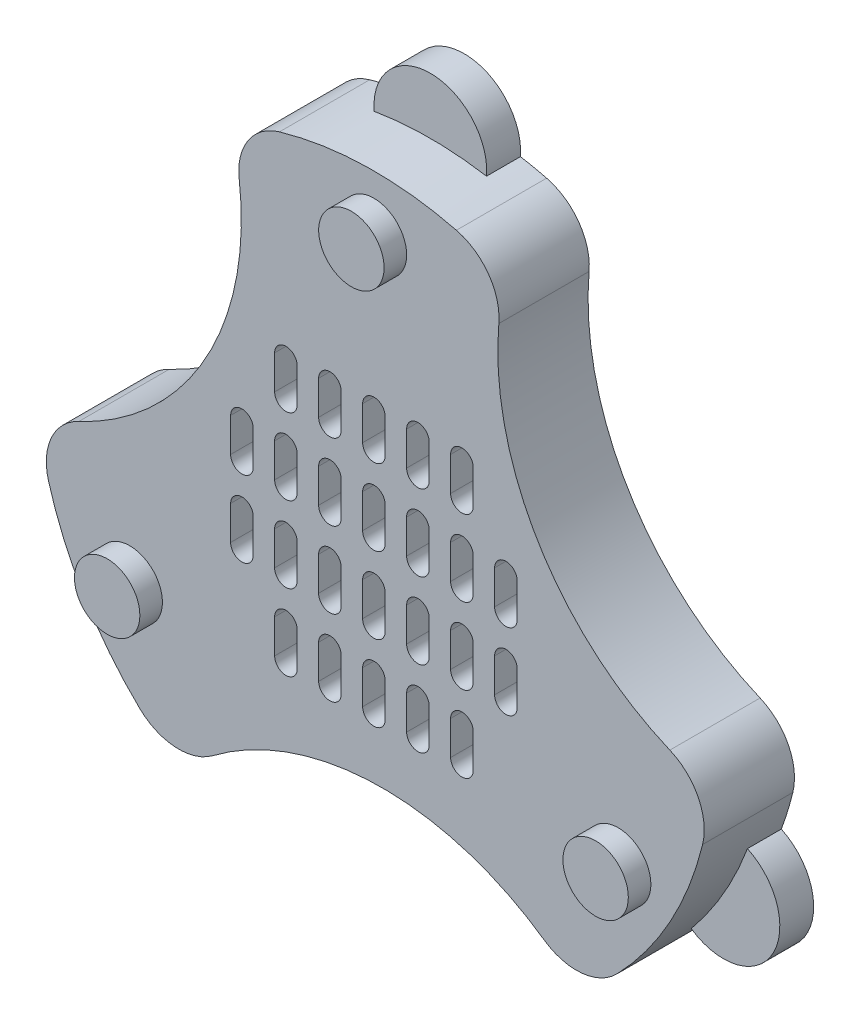
SolidWorks part; units mm, degrees
ref_plane "Спереди" through (0, 0, 0) normal (0, 0, 1) x (1, 0, 0)
ref_plane "Сверху" through (0, 0, 0) normal (0, 1, 0) x (1, 0, 0)
ref_plane "Справа" through (0, 0, 0) normal (1, 0, 0) x (0, 0, -1)
sketch "Sketch1" plane through (0, 0, 0) normal (0, 0, 1) x (1, 0, 0)
  line L0 (3.9, 6.755) -> (7.8, 0) construction
  line L2 (5.85, 10.1325) -> (11.7, 0) construction
  line L4 (7.8, 13.51) -> (15.6, 0) construction
  circle A61 centre (0, 0) radius 20
  circle A131 centre (0, 0) radius 1.25
  circle A484 centre (3.9, 0) radius 1.25
  circle A485 centre (7.8, 0) radius 1.25
  circle A486 centre (11.7, 0) radius 1.25
  circle A487 centre (15.6, 0) radius 1.25
  circle A488 centre (1.95, -3.3775) radius 1.25
  circle A489 centre (3.9, -6.755) radius 1.25
  circle A490 centre (5.85, -10.1325) radius 1.25
  circle A491 centre (7.8, -13.51) radius 1.25
  circle A492 centre (-1.95, -3.3775) radius 1.25
  circle A493 centre (-3.9, -6.755) radius 1.25
  circle A494 centre (-5.85, -10.1325) radius 1.25
  circle A495 centre (-7.8, -13.51) radius 1.25
  circle A496 centre (-3.9, 0) radius 1.25
  circle A497 centre (-7.8, 0) radius 1.25
  circle A498 centre (-11.7, 0) radius 1.25
  circle A499 centre (-15.6, 0) radius 1.25
  circle A500 centre (-1.95, 3.3775) radius 1.25
  circle A501 centre (-3.9, 6.755) radius 1.25
  circle A502 centre (-5.85, 10.1325) radius 1.25
  circle A503 centre (-7.8, 13.51) radius 1.25
  circle A504 centre (1.95, 3.3775) radius 1.25
  circle A505 centre (3.9, 6.755) radius 1.25
  circle A506 centre (5.85, 10.1325) radius 1.25
  circle A507 centre (7.8, 13.51) radius 1.25
  circle A508 centre (5.85, 3.3775) radius 1.25
  circle A509 centre (7.8, 6.755) radius 1.25
  circle A510 centre (9.75, 3.3775) radius 1.25
  circle A511 centre (11.7, 6.755) radius 1.25
  circle A512 centre (9.7491, 10.1341) radius 1.25
  circle A513 centre (13.6509, 3.3759) radius 1.25
  circle A514 centre (5.85, -3.3791) radius 1.25
  circle A515 centre (9.75, -3.3791) radius 1.25
  circle A516 centre (7.8, -6.7566) radius 1.25
  circle A517 centre (11.7, -6.7566) radius 1.25
  circle A518 centre (9.7491, -10.1356) radius 1.25
  circle A519 centre (13.6509, -3.3775) radius 1.25
  circle A520 centre (-0.0013, -6.7573) radius 1.25
  circle A521 centre (1.9487, -10.1348) radius 1.25
  circle A522 centre (-1.9513, -10.1348) radius 1.25
  circle A523 centre (-0.0013, -13.5123) radius 1.25
  circle A524 centre (-3.9032, -13.5123) radius 1.25
  circle A525 centre (3.9005, -13.5123) radius 1.25
  circle A526 centre (-5.8527, -3.3791) radius 1.25
  circle A527 centre (-7.8027, -6.7566) radius 1.25
  circle A528 centre (-9.7527, -3.3791) radius 1.25
  circle A529 centre (-11.7027, -6.7566) radius 1.25
  circle A530 centre (-13.6536, -3.3775) radius 1.25
  circle A531 centre (-9.7518, -10.1356) radius 1.25
  circle A532 centre (-5.8527, 3.3775) radius 1.25
  circle A533 centre (-9.7527, 3.3775) radius 1.25
  circle A534 centre (-7.8027, 6.755) radius 1.25
  circle A535 centre (-11.7027, 6.755) radius 1.25
  circle A536 centre (-9.7518, 10.1341) radius 1.25
  circle A537 centre (-13.6536, 3.3759) radius 1.25
  circle A538 centre (-0.0014, 6.7558) radius 1.25
  circle A539 centre (-1.9514, 10.1333) radius 1.25
  circle A540 centre (1.9486, 10.1333) radius 1.25
  circle A541 centre (-0.0014, 13.5108) radius 1.25
  circle A542 centre (3.9005, 13.5108) radius 1.25
  circle A543 centre (-3.9032, 13.5108) radius 1.25
  circle A544 centre (13.65, -1.1258) radius 2.2517 construction
  circle A545 centre (11.7009, -4.5044) radius 2.2522 construction
  circle A546 centre (9.75, -7.8834) radius 2.2522 construction
  circle A547 centre (7.7987, -11.2591) radius 2.2509 construction
  circle A548 centre (13.65, -1.1258) radius 0.65
  circle A549 centre (11.7009, -4.5044) radius 0.65
  circle A550 centre (9.75, -7.8834) radius 0.65
  circle A551 centre (7.7987, -11.2591) radius 0.65
  circle A552 centre (9.75, -1.1258) radius 0.65
  circle A553 centre (7.8009, -4.5044) radius 0.65
  circle A554 centre (5.85, -7.8834) radius 0.65
  circle A555 centre (3.8987, -11.2591) radius 0.65
  circle A556 centre (5.85, -1.1258) radius 0.65
  circle A557 centre (3.9009, -4.5044) radius 0.65
  circle A558 centre (1.95, -7.8834) radius 0.65
  circle A559 centre (-0.0013, -11.2591) radius 0.65
  circle A560 centre (1.95, -1.1258) radius 0.65
  circle A561 centre (0.0009, -4.5044) radius 0.65
  circle A562 centre (-1.95, -7.8834) radius 0.65
  circle A563 centre (-3.9013, -11.2591) radius 0.65
  circle A564 centre (-1.95, -1.1258) radius 0.65
  circle A565 centre (-3.8991, -4.5044) radius 0.65
  circle A566 centre (-5.85, -7.8834) radius 0.65
  circle A567 centre (-7.8013, -11.2591) radius 0.65
  circle A568 centre (-5.85, -1.1258) radius 0.65
  circle A569 centre (-7.7991, -4.5044) radius 0.65
  circle A570 centre (-9.75, -7.8834) radius 0.65
  circle A572 centre (-9.75, -1.1258) radius 0.65
  circle A573 centre (-11.6991, -4.5044) radius 0.65
  circle A576 centre (-13.65, -1.1258) radius 0.65
  circle A587 centre (0, 2.2517) radius 2.2517 construction
  circle A588 centre (0, 2.2517) radius 0.65
  circle A589 centre (3.9, 2.2517) radius 0.65
  circle A590 centre (7.8, 2.2517) radius 0.65
  circle A591 centre (11.7, 2.2517) radius 0.65
  circle A592 centre (15.6, 2.2517) radius 0.65
  circle A593 centre (1.9491, 5.6297) radius 2.2522 construction
  circle A594 centre (1.9491, 5.6297) radius 0.65
  circle A595 centre (5.8491, 5.6297) radius 0.65
  circle A596 centre (9.7491, 5.6297) radius 0.65
  circle A597 centre (13.6491, 5.6297) radius 0.65
  circle A598 centre (3.8991, 9.0072) radius 2.2522 construction
  circle A599 centre (3.8991, 9.0072) radius 0.65
  circle A600 centre (7.7991, 9.0072) radius 0.65
  circle A601 centre (11.6991, 9.0072) radius 0.65
  circle A602 centre (5.85, 12.3842) radius 2.2517 construction
  circle A603 centre (5.85, 12.3842) radius 0.65
  circle A604 centre (9.75, 12.3842) radius 0.65
  circle A605 centre (5.85, -14.6358) radius 0.65
  circle A606 centre (1.9509, -14.6353) radius 0.65
  circle A607 centre (-1.9491, -14.6353) radius 0.65
  circle A608 centre (-5.85, -14.6358) radius 0.65
  circle A609 centre (-15.6, 2.2517) radius 0.65
  circle A610 centre (-13.65, 5.6281) radius 0.65
  circle A611 centre (-11.7, 9.0056) radius 0.65
  circle A612 centre (-9.75, 12.3842) radius 0.65
  circle A613 centre (-5.85, 12.3842) radius 0.65
  circle A614 centre (-1.95, 12.3842) radius 0.65
  circle A615 centre (1.95, 12.3842) radius 0.65
  circle A616 centre (-7.8, 9.0056) radius 0.65
  circle A617 centre (-9.75, 5.6281) radius 0.65
  circle A618 centre (-11.7, 2.2517) radius 0.65
  circle A619 centre (-3.9, 9.0056) radius 0.65
  circle A620 centre (-5.85, 5.6281) radius 0.65
  circle A621 centre (-7.8, 2.2517) radius 0.65
  circle A622 centre (0, 9.0056) radius 0.65
  circle A623 centre (-1.95, 5.6281) radius 0.65
  circle A624 centre (-3.9, 2.2517) radius 0.65
  circle A625 centre (-15.5991, -4.5044) radius 0.65
  circle A626 centre (-13.65, -7.8834) radius 0.65
  circle A627 centre (-17.55, -7.8834) radius 0.65
  circle A628 centre (-19.5013, -11.2591) radius 0.65
  circle A629 centre (-15.6013, -11.2591) radius 0.65
  circle A630 centre (-11.7013, -11.2591) radius 0.65
  point P51 (0, 0)
  point P125 (-0.0013, -0.0008)
  point P231 (0, 0)
  dimension "D1" = 5
  dimension "D3" = 6
  dimension "D5" = 8
  dimension "D7" = 4
  dimension "D11" = 4
  dimension "D2" = 6
  dimension "D6" = 5
  dimension "D8" = 3
  dimension "D9" = 2
  dimension "D4" = 1.3
  dimension "D10" = 3
ref_plane "Plane1" through (0, 0, 10) normal (0, 0, 1) x (1, 0, 0)
sketch "Sketch2" plane through (0, 0, 10) normal (0, 0, 1) x (1, 0, 0)
  line L0 (-7.8, 13.51) -> (-7.8027, 6.755) construction
  line L1 (-9.7518, 10.1341) -> (-5.85, 10.1325) construction
  line L2 (-7.8008, 11.6325) -> (-7.8019, 8.6325) construction
  line L3 (-6.8008, 11.6321) -> (-6.8019, 8.6321)
  line L4 (-8.8008, 11.6329) -> (-8.8019, 8.6329)
  line L5 (-4.9008, 11.6329) -> (-4.9019, 8.6329)
  line L6 (-2.9008, 11.6321) -> (-2.9019, 8.6321)
  line L7 (-3.9008, 11.6325) -> (-3.9019, 8.6325) construction
  line L8 (-1.0008, 11.6329) -> (-1.0019, 8.6329)
  line L9 (0.9992, 11.6321) -> (0.9981, 8.6321)
  line L10 (-0.0008, 11.6325) -> (-0.0019, 8.6325) construction
  line L11 (2.8992, 11.6329) -> (2.8981, 8.6329)
  line L12 (4.8992, 11.6321) -> (4.8981, 8.6321)
  line L13 (3.8992, 11.6325) -> (3.8981, 8.6325) construction
  line L14 (6.7992, 11.6329) -> (6.7981, 8.6329)
  line L15 (8.7992, 11.6321) -> (8.7981, 8.6321)
  line L16 (7.7992, 11.6325) -> (7.7981, 8.6325) construction
  line L17 (-9.7518, 10.1341) -> (-9.7527, 3.3775) construction
  line L18 (-11.7027, 6.755) -> (-7.8027, 6.755) construction
  line L19 (-10.7035, 1.877) -> (-10.702, 4.877)
  line L22 (-9.7527, 3.3775) -> (-5.8527, 3.3775) construction
  line L25 (-7.8027, 6.755) -> (-7.8, 0) construction
  line L26 (-7.8035, 1.8775) -> (-7.8019, 4.8775) construction
  line L27 (-8.8035, 1.878) -> (-8.8019, 4.878)
  line L28 (-6.8035, 1.877) -> (-6.8019, 4.877)
  line L29 (-2.9035, 1.877) -> (-2.9019, 4.877)
  line L30 (-4.9035, 1.878) -> (-4.9019, 4.878)
  line L31 (-3.9035, 1.8775) -> (-3.9019, 4.8775) construction
  line L32 (0.9965, 1.877) -> (0.9981, 4.877)
  line L33 (-1.0035, 1.878) -> (-1.0019, 4.878)
  line L34 (-0.0035, 1.8775) -> (-0.0019, 4.8775) construction
  line L35 (4.8965, 1.877) -> (4.8981, 4.877)
  line L36 (2.8965, 1.878) -> (2.8981, 4.878)
  line L37 (3.8965, 1.8775) -> (3.8981, 4.8775) construction
  line L38 (8.7965, 1.877) -> (8.7981, 4.877)
  line L39 (6.7965, 1.878) -> (6.7981, 4.878)
  line L40 (7.7965, 1.8775) -> (7.7981, 4.8775) construction
  line L41 (12.6965, 1.877) -> (12.6981, 4.877)
  line L42 (10.6965, 1.878) -> (10.6981, 4.878)
  line L43 (11.6965, 1.8775) -> (11.6981, 4.8775) construction
  line L44 (-12.7035, 1.878) -> (-12.7019, 4.878)
  line L45 (-11.7035, 1.8775) -> (-11.702, 4.8775) construction
  line L46 (-9.7527, -3.3791) -> (-5.8527, -3.3791) construction
  line L47 (-7.8, 0) -> (-7.8027, -6.7566) construction
  line L48 (-7.8046, -4.8791) -> (-7.8008, -1.8791) construction
  line L49 (-8.8046, -4.8778) -> (-8.8008, -1.8778)
  line L50 (-6.8046, -4.8804) -> (-6.8008, -1.8804)
  line L51 (-2.9046, -4.8804) -> (-2.9008, -1.8804)
  line L52 (-4.9046, -4.8778) -> (-4.9008, -1.8778)
  line L53 (-3.9046, -4.8791) -> (-3.9008, -1.8791) construction
  line L54 (0.9954, -4.8804) -> (0.9992, -1.8804)
  line L55 (-1.0046, -4.8778) -> (-1.0008, -1.8778)
  line L56 (-0.0046, -4.8791) -> (-0.0008, -1.8791) construction
  line L57 (4.8954, -4.8804) -> (4.8992, -1.8804)
  line L58 (2.8954, -4.8778) -> (2.8992, -1.8778)
  line L59 (3.8954, -4.8791) -> (3.8992, -1.8791) construction
  line L60 (8.7954, -4.8804) -> (8.7992, -1.8804)
  line L61 (6.7954, -4.8778) -> (6.7992, -1.8778)
  line L62 (7.7954, -4.8791) -> (7.7992, -1.8791) construction
  line L63 (12.6954, -4.8804) -> (12.6992, -1.8804)
  line L64 (10.6954, -4.8778) -> (10.6992, -1.8778)
  line L65 (11.6954, -4.8791) -> (11.6992, -1.8791) construction
  line L66 (-10.7046, -4.8804) -> (-10.7008, -1.8804)
  line L67 (-12.7046, -4.8778) -> (-12.7008, -1.8778)
  line L68 (-11.7046, -4.8791) -> (-11.7008, -1.8791) construction
  line L69 (-9.7518, -10.1356) -> (-5.482, -10.1356) construction
  line L70 (-7.8027, -6.7566) -> (-7.8, -13.51) construction
  line L71 (-7.8007, -8.6356) -> (-7.8007, -11.6356) construction
  line L72 (-6.8007, -8.6356) -> (-6.8007, -11.6356)
  line L73 (-8.8007, -8.6356) -> (-8.8007, -11.6356)
  line L74 (-4.9007, -8.6356) -> (-4.9007, -11.6356)
  line L75 (-2.9007, -8.6356) -> (-2.9007, -11.6356)
  line L76 (-3.9007, -8.6356) -> (-3.9007, -11.6356) construction
  line L77 (-1.0007, -8.6356) -> (-1.0007, -11.6356)
  line L78 (0.9993, -8.6356) -> (0.9993, -11.6356)
  line L79 (-0.0007, -8.6356) -> (-0.0007, -11.6356) construction
  line L80 (2.8993, -8.6356) -> (2.8993, -11.6356)
  line L81 (4.8993, -8.6356) -> (4.8993, -11.6356)
  line L82 (3.8993, -8.6356) -> (3.8993, -11.6356) construction
  line L83 (6.7993, -8.6356) -> (6.7993, -11.6356)
  line L84 (8.7993, -8.6356) -> (8.7993, -11.6356)
  line L85 (7.7993, -8.6356) -> (7.7993, -11.6356) construction
  arc A0 (-6.8008, 11.6321) -> (-8.8008, 11.6329) centre (-7.8008, 11.6325) ccw
  arc A1 (-8.8019, 8.6329) -> (-6.8019, 8.6321) centre (-7.8019, 8.6325) ccw
  arc A2 (-2.9008, 11.6321) -> (-4.9008, 11.6329) centre (-3.9008, 11.6325) ccw
  arc A3 (-4.9019, 8.6329) -> (-2.9019, 8.6321) centre (-3.9019, 8.6325) ccw
  arc A4 (0.9992, 11.6321) -> (-1.0008, 11.6329) centre (-0.0008, 11.6325) ccw
  arc A5 (-1.0019, 8.6329) -> (0.9981, 8.6321) centre (-0.0019, 8.6325) ccw
  arc A6 (4.8992, 11.6321) -> (2.8992, 11.6329) centre (3.8992, 11.6325) ccw
  arc A7 (2.8981, 8.6329) -> (4.8981, 8.6321) centre (3.8981, 8.6325) ccw
  arc A8 (8.7992, 11.6321) -> (6.7992, 11.6329) centre (7.7992, 11.6325) ccw
  arc A9 (6.7981, 8.6329) -> (8.7981, 8.6321) centre (7.7981, 8.6325) ccw
  arc A14 (-8.8035, 1.878) -> (-6.8035, 1.877) centre (-7.8035, 1.8775) ccw
  arc A15 (-6.8019, 4.877) -> (-8.8019, 4.878) centre (-7.8019, 4.8775) ccw
  arc A16 (-4.9035, 1.878) -> (-2.9035, 1.877) centre (-3.9035, 1.8775) ccw
  arc A17 (-2.9019, 4.877) -> (-4.9019, 4.878) centre (-3.9019, 4.8775) ccw
  arc A18 (-1.0035, 1.878) -> (0.9965, 1.877) centre (-0.0035, 1.8775) ccw
  arc A19 (0.9981, 4.877) -> (-1.0019, 4.878) centre (-0.0019, 4.8775) ccw
  arc A20 (2.8965, 1.878) -> (4.8965, 1.877) centre (3.8965, 1.8775) ccw
  arc A21 (4.8981, 4.877) -> (2.8981, 4.878) centre (3.8981, 4.8775) ccw
  arc A22 (6.7965, 1.878) -> (8.7965, 1.877) centre (7.7965, 1.8775) ccw
  arc A23 (8.7981, 4.877) -> (6.7981, 4.878) centre (7.7981, 4.8775) ccw
  arc A24 (10.6965, 1.878) -> (12.6965, 1.877) centre (11.6965, 1.8775) ccw
  arc A25 (12.6981, 4.877) -> (10.6981, 4.878) centre (11.6981, 4.8775) ccw
  arc A26 (-12.7035, 1.878) -> (-10.7035, 1.877) centre (-11.7035, 1.8775) ccw
  arc A27 (-10.702, 4.877) -> (-12.7019, 4.878) centre (-11.702, 4.8775) ccw
  arc A28 (-8.8046, -4.8778) -> (-6.8046, -4.8804) centre (-7.8046, -4.8791) ccw
  arc A29 (-6.8008, -1.8804) -> (-8.8008, -1.8778) centre (-7.8008, -1.8791) ccw
  arc A30 (-4.9046, -4.8778) -> (-2.9046, -4.8804) centre (-3.9046, -4.8791) ccw
  arc A31 (-2.9008, -1.8804) -> (-4.9008, -1.8778) centre (-3.9008, -1.8791) ccw
  arc A32 (-1.0046, -4.8778) -> (0.9954, -4.8804) centre (-0.0046, -4.8791) ccw
  arc A33 (0.9992, -1.8804) -> (-1.0008, -1.8778) centre (-0.0008, -1.8791) ccw
  arc A34 (2.8954, -4.8778) -> (4.8954, -4.8804) centre (3.8954, -4.8791) ccw
  arc A35 (4.8992, -1.8804) -> (2.8992, -1.8778) centre (3.8992, -1.8791) ccw
  arc A36 (6.7954, -4.8778) -> (8.7954, -4.8804) centre (7.7954, -4.8791) ccw
  arc A37 (8.7992, -1.8804) -> (6.7992, -1.8778) centre (7.7992, -1.8791) ccw
  arc A38 (10.6954, -4.8778) -> (12.6954, -4.8804) centre (11.6954, -4.8791) ccw
  arc A39 (12.6992, -1.8804) -> (10.6992, -1.8778) centre (11.6992, -1.8791) ccw
  arc A40 (-12.7046, -4.8778) -> (-10.7046, -4.8804) centre (-11.7046, -4.8791) ccw
  arc A41 (-10.7008, -1.8804) -> (-12.7008, -1.8778) centre (-11.7008, -1.8791) ccw
  arc A42 (-6.8007, -8.6356) -> (-8.8007, -8.6356) centre (-7.8007, -8.6356) ccw
  arc A43 (-8.8007, -11.6356) -> (-6.8007, -11.6356) centre (-7.8007, -11.6356) ccw
  arc A44 (-2.9007, -8.6356) -> (-4.9007, -8.6356) centre (-3.9007, -8.6356) ccw
  arc A45 (-4.9007, -11.6356) -> (-2.9007, -11.6356) centre (-3.9007, -11.6356) ccw
  arc A46 (0.9993, -8.6356) -> (-1.0007, -8.6356) centre (-0.0007, -8.6356) ccw
  arc A47 (-1.0007, -11.6356) -> (0.9993, -11.6356) centre (-0.0007, -11.6356) ccw
  arc A48 (4.8993, -8.6356) -> (2.8993, -8.6356) centre (3.8993, -8.6356) ccw
  arc A49 (2.8993, -11.6356) -> (4.8993, -11.6356) centre (3.8993, -11.6356) ccw
  arc A50 (8.7993, -8.6356) -> (6.7993, -8.6356) centre (7.7993, -8.6356) ccw
  arc A51 (6.7993, -11.6356) -> (8.7993, -11.6356) centre (7.7993, -11.6356) ccw
  circle A52 centre (0, 0) radius 16.85 construction
  circle A53 centre (0, 0) radius 18.85
  point P10 (-7.8014, 10.1325)
  point P18 (-3.9014, 10.1325)
  point P25 (-0.0014, 10.1325)
  point P32 (3.8986, 10.1325)
  point P39 (7.7986, 10.1325)
  point P50 (-11.7027, 3.3775)
  point P58 (-7.8027, 3.3775)
  point P68 (-3.9027, 3.3775)
  point P75 (-0.0027, 3.3775)
  point P82 (3.8973, 3.3775)
  point P89 (7.7973, 3.3775)
  point P96 (11.6973, 3.3775)
  point P108 (-7.8027, -3.3791)
  point P116 (-3.9027, -3.3791)
  point P123 (-0.0027, -3.3791)
  point P130 (3.8973, -3.3791)
  point P137 (7.7973, -3.3791)
  point P144 (11.6973, -3.3791)
  point P151 (-11.7027, -3.3791)
  point P162 (-7.8007, -10.1356)
  point P170 (-3.9007, -10.1356)
  point P177 (-0.0007, -10.1356)
  point P184 (3.8993, -10.1356)
  point P191 (7.7993, -10.1356)
  dimension "D1" = 2
  dimension "D15" = 2
  dimension "D2" = 3
  dimension "D4" = 2
  dimension "D5" = 3
  dimension "D6" = 2
  dimension "D7" = 3
  dimension "D9" = 2
  dimension "D12" = 3
  dimension "D13" = 2
  dimension "D3" = 5
  dimension "D8" = 6
  dimension "D10" = 6
  dimension "D11" = 2
  dimension "D14" = 5
extrude "Boss-Extrude1" add sketch "Sketch2" along normal blind 8
sketch "Sketch3" plane through (0, 0, 18) normal (0, 0, 1) x (1, 0, 0)
  circle A0 centre (0, 0) radius 17.6
  circle A1 centre (0, 0) radius 30
extrude "Boss-Extrude2" add sketch "Sketch3" against normal up to surface (8 mm away) up to face at (3.8993, -10.1356, 10)
sketch "Sketch4" plane through (0, 0, 18) normal (0, 0, 1) x (1, 0, 0)
  circle A0 centre (0, 0) radius 25 construction
  circle A1 centre (0, 25) radius 2.9
  circle A2 centre (21.6506, -12.5) radius 2.9
  circle A3 centre (-21.6506, -12.5) radius 2.9
  point P11 (0, 0)
  dimension "D1" = 3
extrude "Boss-Extrude3" add sketch "Sketch4" along normal blind 2
sketch "Sketch6" plane through (0, 0, 10) normal (0, 0, -1) x (-1, 0, 0)
  circle A0 centre (0, 30) radius 5
  circle A1 centre (0, 0) radius 30 construction
  circle A2 centre (25.9808, -15) radius 5
  circle A3 centre (-25.9808, -15) radius 5
  point P10 (0, 0)
  dimension "D1" = 3
extrude "Boss-Extrude4" add sketch "Sketch6" against normal blind 3
sketch "Sketch5" plane through (0, 0, 10) normal (0, 0, -1) x (-1, 0, 0)
  circle A0 centre (0, 25) radius 3
  circle A1 centre (21.6506, -12.5) radius 3
  circle A2 centre (-21.6506, -12.5) radius 3
extrude "Cut-Extrude1" cut sketch "Sketch5" against normal blind 3
sketch "Sketch7" plane through (0, 0, 10) normal (0, 0, -1) x (-1, 0, 0)
  line L0 (0, 0) -> (-35.9801, 21.6664) construction
  circle A0 centre (0, 0) radius 42 construction
  circle A1 centre (-35.9801, 21.6664) radius 25
  circle A2 centre (36.7537, 20.3265) radius 25
  circle A3 centre (-0.7736, -41.9929) radius 25
  point P11 (0, 0)
  dimension "D1" = 3
extrude "Cut-Extrude2" cut sketch "Sketch7" against normal blind 8
fillet "Fillet1" radius 5 6 edges at (-29.7735, -3.6793, 14) (-12.7099, 27.1746, 14) (18.0731, -23.945, 14) (-17.1789, -24.5944, 14) (11.7004, 27.6243, 14) (29.8888, -2.5802, 14)
sketch "Sketch8"
sketch_block_instance "Block1-1"
sketch_block "Block1" parameters "D1"=2, "D2"=3
sketch_block_instance "Block3-1"
sketch_block "Block3" parameters "D1"=2, "D2"=3
sketch "Sketch9" plane through (0, 0, 0) normal (0, 0, 1) x (1, 0, 0)
  line L0 (-7.8, 13.51) -> (-7.8027, 6.755) construction
  line L1 (-9.7518, 10.1341) -> (-5.85, 10.1325) construction
  line L2 (-7.8008, 11.6325) -> (-7.8019, 8.6325) construction
  line L3 (-6.8008, 11.6321) -> (-6.8019, 8.6321)
  line L4 (-8.8008, 11.6329) -> (-8.8019, 8.6329)
  line L5 (-4.9008, 11.6329) -> (-4.9019, 8.6329)
  line L6 (-2.9008, 11.6321) -> (-2.9019, 8.6321)
  line L7 (-3.9008, 11.6325) -> (-3.9019, 8.6325) construction
  line L8 (-1.0008, 11.6329) -> (-1.0019, 8.6329)
  line L9 (0.9992, 11.6321) -> (0.9981, 8.6321)
  line L10 (-0.0008, 11.6325) -> (-0.0019, 8.6325) construction
  line L11 (2.8992, 11.6329) -> (2.8981, 8.6329)
  line L12 (4.8992, 11.6321) -> (4.8981, 8.6321)
  line L13 (3.8992, 11.6325) -> (3.8981, 8.6325) construction
  line L14 (6.7992, 11.6329) -> (6.7981, 8.6329)
  line L15 (8.7992, 11.6321) -> (8.7981, 8.6321)
  line L16 (7.7992, 11.6325) -> (7.7981, 8.6325) construction
  line L17 (-9.7518, 10.1341) -> (-9.7527, 3.3775) construction
  line L18 (-11.7027, 6.755) -> (-7.8027, 6.755) construction
  line L19 (-10.7035, 1.877) -> (-10.702, 4.877)
  line L22 (-9.7527, 3.3775) -> (-5.8527, 3.3775) construction
  line L25 (-7.8027, 6.755) -> (-7.8, 0) construction
  line L26 (-7.8035, 1.8775) -> (-7.8019, 4.8775) construction
  line L27 (-8.8035, 1.878) -> (-8.8019, 4.878)
  line L28 (-6.8035, 1.877) -> (-6.8019, 4.877)
  line L29 (-2.9035, 1.877) -> (-2.9019, 4.877)
  line L30 (-4.9035, 1.878) -> (-4.9019, 4.878)
  line L31 (-3.9035, 1.8775) -> (-3.9019, 4.8775) construction
  line L32 (0.9965, 1.877) -> (0.9981, 4.877)
  line L33 (-1.0035, 1.878) -> (-1.0019, 4.878)
  line L34 (-0.0035, 1.8775) -> (-0.0019, 4.8775) construction
  line L35 (4.8965, 1.877) -> (4.8981, 4.877)
  line L36 (2.8965, 1.878) -> (2.8981, 4.878)
  line L37 (3.8965, 1.8775) -> (3.8981, 4.8775) construction
  line L38 (8.7965, 1.877) -> (8.7981, 4.877)
  line L39 (6.7965, 1.878) -> (6.7981, 4.878)
  line L40 (7.7965, 1.8775) -> (7.7981, 4.8775) construction
  line L41 (12.6965, 1.877) -> (12.6981, 4.877)
  line L42 (10.6965, 1.878) -> (10.6981, 4.878)
  line L43 (11.6965, 1.8775) -> (11.6981, 4.8775) construction
  line L44 (-12.7035, 1.878) -> (-12.7019, 4.878)
  line L45 (-11.7035, 1.8775) -> (-11.702, 4.8775) construction
  line L46 (-9.7527, -3.3791) -> (-5.8527, -3.3791) construction
  line L47 (-7.8, 0) -> (-7.8027, -6.7566) construction
  line L48 (-7.8046, -4.8791) -> (-7.8008, -1.8791) construction
  line L49 (-8.8046, -4.8778) -> (-8.8008, -1.8778)
  line L50 (-6.8046, -4.8804) -> (-6.8008, -1.8804)
  line L51 (-2.9046, -4.8804) -> (-2.9008, -1.8804)
  line L52 (-4.9046, -4.8778) -> (-4.9008, -1.8778)
  line L53 (-3.9046, -4.8791) -> (-3.9008, -1.8791) construction
  line L54 (0.9954, -4.8804) -> (0.9992, -1.8804)
  line L55 (-1.0046, -4.8778) -> (-1.0008, -1.8778)
  line L56 (-0.0046, -4.8791) -> (-0.0008, -1.8791) construction
  line L57 (4.8954, -4.8804) -> (4.8992, -1.8804)
  line L58 (2.8954, -4.8778) -> (2.8992, -1.8778)
  line L59 (3.8954, -4.8791) -> (3.8992, -1.8791) construction
  line L60 (8.7954, -4.8804) -> (8.7992, -1.8804)
  line L61 (6.7954, -4.8778) -> (6.7992, -1.8778)
  line L62 (7.7954, -4.8791) -> (7.7992, -1.8791) construction
  line L63 (12.6954, -4.8804) -> (12.6992, -1.8804)
  line L64 (10.6954, -4.8778) -> (10.6992, -1.8778)
  line L65 (11.6954, -4.8791) -> (11.6992, -1.8791) construction
  line L66 (-10.7046, -4.8804) -> (-10.7008, -1.8804)
  line L67 (-12.7046, -4.8778) -> (-12.7008, -1.8778)
  line L68 (-11.7046, -4.8791) -> (-11.7008, -1.8791) construction
  line L69 (-9.7518, -10.1356) -> (-5.482, -10.1356) construction
  line L70 (-7.8027, -6.7566) -> (-7.8, -13.51) construction
  line L71 (-7.8007, -8.6356) -> (-7.8007, -11.6356) construction
  line L72 (-6.8007, -8.6356) -> (-6.8007, -11.6356)
  line L73 (-8.8007, -8.6356) -> (-8.8007, -11.6356)
  line L74 (-4.9007, -8.6356) -> (-4.9007, -11.6356)
  line L75 (-2.9007, -8.6356) -> (-2.9007, -11.6356)
  line L76 (-3.9007, -8.6356) -> (-3.9007, -11.6356) construction
  line L77 (-1.0007, -8.6356) -> (-1.0007, -11.6356)
  line L78 (0.9993, -8.6356) -> (0.9993, -11.6356)
  line L79 (-0.0007, -8.6356) -> (-0.0007, -11.6356) construction
  line L80 (2.8993, -8.6356) -> (2.8993, -11.6356)
  line L81 (4.8993, -8.6356) -> (4.8993, -11.6356)
  line L82 (3.8993, -8.6356) -> (3.8993, -11.6356) construction
  line L83 (6.7993, -8.6356) -> (6.7993, -11.6356)
  line L84 (8.7993, -8.6356) -> (8.7993, -11.6356)
  line L85 (7.7993, -8.6356) -> (7.7993, -11.6356) construction
  arc A0 (-6.8008, 11.6321) -> (-8.8008, 11.6329) centre (-7.8008, 11.6325) ccw
  arc A1 (-8.8019, 8.6329) -> (-6.8019, 8.6321) centre (-7.8019, 8.6325) ccw
  arc A2 (-2.9008, 11.6321) -> (-4.9008, 11.6329) centre (-3.9008, 11.6325) ccw
  arc A3 (-4.9019, 8.6329) -> (-2.9019, 8.6321) centre (-3.9019, 8.6325) ccw
  arc A4 (0.9992, 11.6321) -> (-1.0008, 11.6329) centre (-0.0008, 11.6325) ccw
  arc A5 (-1.0019, 8.6329) -> (0.9981, 8.6321) centre (-0.0019, 8.6325) ccw
  arc A6 (4.8992, 11.6321) -> (2.8992, 11.6329) centre (3.8992, 11.6325) ccw
  arc A7 (2.8981, 8.6329) -> (4.8981, 8.6321) centre (3.8981, 8.6325) ccw
  arc A8 (8.7992, 11.6321) -> (6.7992, 11.6329) centre (7.7992, 11.6325) ccw
  arc A9 (6.7981, 8.6329) -> (8.7981, 8.6321) centre (7.7981, 8.6325) ccw
  arc A14 (-8.8035, 1.878) -> (-6.8035, 1.877) centre (-7.8035, 1.8775) ccw
  arc A15 (-6.8019, 4.877) -> (-8.8019, 4.878) centre (-7.8019, 4.8775) ccw
  arc A16 (-4.9035, 1.878) -> (-2.9035, 1.877) centre (-3.9035, 1.8775) ccw
  arc A17 (-2.9019, 4.877) -> (-4.9019, 4.878) centre (-3.9019, 4.8775) ccw
  arc A18 (-1.0035, 1.878) -> (0.9965, 1.877) centre (-0.0035, 1.8775) ccw
  arc A19 (0.9981, 4.877) -> (-1.0019, 4.878) centre (-0.0019, 4.8775) ccw
  arc A20 (2.8965, 1.878) -> (4.8965, 1.877) centre (3.8965, 1.8775) ccw
  arc A21 (4.8981, 4.877) -> (2.8981, 4.878) centre (3.8981, 4.8775) ccw
  arc A22 (6.7965, 1.878) -> (8.7965, 1.877) centre (7.7965, 1.8775) ccw
  arc A23 (8.7981, 4.877) -> (6.7981, 4.878) centre (7.7981, 4.8775) ccw
  arc A24 (10.6965, 1.878) -> (12.6965, 1.877) centre (11.6965, 1.8775) ccw
  arc A25 (12.6981, 4.877) -> (10.6981, 4.878) centre (11.6981, 4.8775) ccw
  arc A26 (-12.7035, 1.878) -> (-10.7035, 1.877) centre (-11.7035, 1.8775) ccw
  arc A27 (-10.702, 4.877) -> (-12.7019, 4.878) centre (-11.702, 4.8775) ccw
  arc A28 (-8.8046, -4.8778) -> (-6.8046, -4.8804) centre (-7.8046, -4.8791) ccw
  arc A29 (-6.8008, -1.8804) -> (-8.8008, -1.8778) centre (-7.8008, -1.8791) ccw
  arc A30 (-4.9046, -4.8778) -> (-2.9046, -4.8804) centre (-3.9046, -4.8791) ccw
  arc A31 (-2.9008, -1.8804) -> (-4.9008, -1.8778) centre (-3.9008, -1.8791) ccw
  arc A32 (-1.0046, -4.8778) -> (0.9954, -4.8804) centre (-0.0046, -4.8791) ccw
  arc A33 (0.9992, -1.8804) -> (-1.0008, -1.8778) centre (-0.0008, -1.8791) ccw
  arc A34 (2.8954, -4.8778) -> (4.8954, -4.8804) centre (3.8954, -4.8791) ccw
  arc A35 (4.8992, -1.8804) -> (2.8992, -1.8778) centre (3.8992, -1.8791) ccw
  arc A36 (6.7954, -4.8778) -> (8.7954, -4.8804) centre (7.7954, -4.8791) ccw
  arc A37 (8.7992, -1.8804) -> (6.7992, -1.8778) centre (7.7992, -1.8791) ccw
  arc A38 (10.6954, -4.8778) -> (12.6954, -4.8804) centre (11.6954, -4.8791) ccw
  arc A39 (12.6992, -1.8804) -> (10.6992, -1.8778) centre (11.6992, -1.8791) ccw
  arc A40 (-12.7046, -4.8778) -> (-10.7046, -4.8804) centre (-11.7046, -4.8791) ccw
  arc A41 (-10.7008, -1.8804) -> (-12.7008, -1.8778) centre (-11.7008, -1.8791) ccw
  arc A42 (-6.8007, -8.6356) -> (-8.8007, -8.6356) centre (-7.8007, -8.6356) ccw
  arc A43 (-8.8007, -11.6356) -> (-6.8007, -11.6356) centre (-7.8007, -11.6356) ccw
  arc A44 (-2.9007, -8.6356) -> (-4.9007, -8.6356) centre (-3.9007, -8.6356) ccw
  arc A45 (-4.9007, -11.6356) -> (-2.9007, -11.6356) centre (-3.9007, -11.6356) ccw
  arc A46 (0.9993, -8.6356) -> (-1.0007, -8.6356) centre (-0.0007, -8.6356) ccw
  arc A47 (-1.0007, -11.6356) -> (0.9993, -11.6356) centre (-0.0007, -11.6356) ccw
  arc A48 (4.8993, -8.6356) -> (2.8993, -8.6356) centre (3.8993, -8.6356) ccw
  arc A49 (2.8993, -11.6356) -> (4.8993, -11.6356) centre (3.8993, -11.6356) ccw
  arc A50 (8.7993, -8.6356) -> (6.7993, -8.6356) centre (7.7993, -8.6356) ccw
  arc A51 (6.7993, -11.6356) -> (8.7993, -11.6356) centre (7.7993, -11.6356) ccw
  circle A52 centre (0, 0) radius 16.85 construction
  circle A53 centre (0, 0) radius 18.85
  point P10 (-7.8014, 10.1325)
  point P18 (-3.9014, 10.1325)
  point P25 (-0.0014, 10.1325)
  point P32 (3.8986, 10.1325)
  point P39 (7.7986, 10.1325)
  point P50 (-11.7027, 3.3775)
  point P58 (-7.8027, 3.3775)
  point P68 (-3.9027, 3.3775)
  point P75 (-0.0027, 3.3775)
  point P82 (3.8973, 3.3775)
  point P89 (7.7973, 3.3775)
  point P96 (11.6973, 3.3775)
  point P108 (-7.8027, -3.3791)
  point P116 (-3.9027, -3.3791)
  point P123 (-0.0027, -3.3791)
  point P130 (3.8973, -3.3791)
  point P137 (7.7973, -3.3791)
  point P144 (11.6973, -3.3791)
  point P151 (-11.7027, -3.3791)
  point P162 (-7.8007, -10.1356)
  point P170 (-3.9007, -10.1356)
  point P177 (-0.0007, -10.1356)
  point P184 (3.8993, -10.1356)
  point P191 (7.7993, -10.1356)
  dimension "D1" = 2
  dimension "D15" = 2
  dimension "D2" = 3
  dimension "D4" = 2
  dimension "D5" = 3
  dimension "D6" = 2
  dimension "D7" = 3
  dimension "D9" = 2
  dimension "D12" = 3
  dimension "D13" = 2
  dimension "D3" = 5
  dimension "D8" = 6
  dimension "D10" = 6
  dimension "D11" = 2
  dimension "D14" = 5
